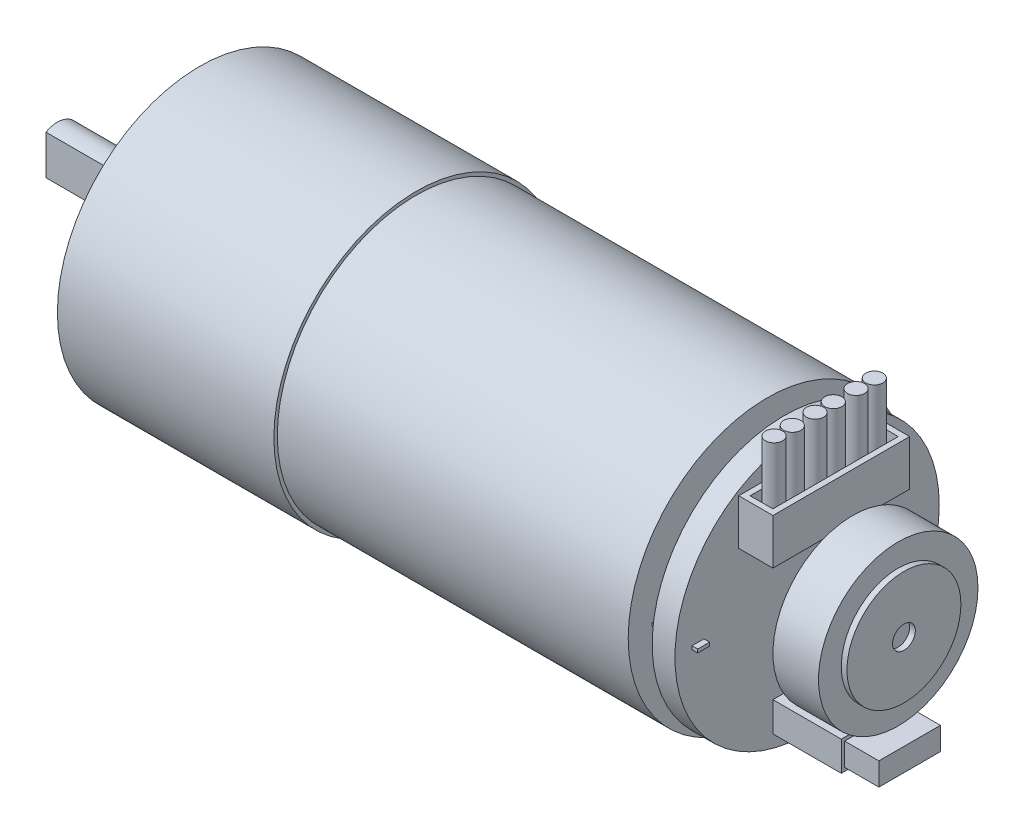
SolidWorks part; units mm, degrees
ref_plane "Alzado" through (0, 0, 0) normal (0, 0, 1) x (1, 0, 0)
ref_plane "Planta" through (0, 0, 0) normal (0, 1, 0) x (1, 0, 0)
ref_plane "Vista lateral" through (0, 0, 0) normal (1, 0, 0) x (0, 0, -1)
sketch "Croquis1" plane through (0, 0, 0) normal (0, 0, 1) x (1, 0, 0)
  line L0 (0, 0) -> (30.8, 0) construction
  line L1 (0, 0) -> (0, 12.2)
  line L2 (0, 12.2) -> (30.8, 12.2)
  line L3 (30.8, 12.2) -> (30.8, 0)
  dimension "D1" = 30.8
  dimension "D2" = 12.2
revolve "Revolución-Lámina1" add sketch "Croquis1" angle 360 about L0
sketch "Croquis3" plane through (0, 0, 0) normal (-1, 0, 0) x (0, 0, 1)
  circle A0 centre (0, 0) radius 12.5
  dimension "D1" = 25
extrude "Saliente-Extruir1" add sketch "Croquis3" along normal blind 19
ref_plane "Plano1" through (30.8, 0, 0) normal (1, 0, 0) x (0, 0, -1)
ref_plane "Plano3" through (-19, 0, 0) normal (1, 0, 0) x (0, 0, -1)
ref_plane "Plano4" through (-15.5, 0, 0) normal (1, 0, 0) x (0, 0, -1)
sketch "Croquis6" plane through (-15.5, 0, 0) normal (1, 0, 0) x (0, 0, -1)
  circle A0 centre (0, 0) radius 12
  circle A1 centre (0, 0) radius 12.5
  dimension "D1" = 24
  dimension "D2" = 25
extrude "Cortar-Extruir3" [suppressed] cut sketch "Croquis6" against normal blind 1
ref_plane "Plano5" through (-1.5, 0, 0) normal (1, 0, 0) x (0, 0, -1)
sketch "Croquis7" plane through (-1.5, 0, 0) normal (1, 0, 0) x (0, 0, -1)
  circle A0 centre (0, 0) radius 12.5
  circle A1 centre (0, 0) radius 12
  dimension "D1" = 24
  dimension "D2" = 25
extrude "Cortar-Extruir4" [suppressed] cut sketch "Croquis7" against normal blind 1
sketch "Croquis8" plane through (-19, 0, 0) normal (-1, 0, 0) x (0, 0, 1)
  circle A0 centre (0, 0) radius 3.5
  dimension "D1" = 7
extrude "Saliente-Extruir3" add sketch "Croquis8" along normal blind 2.5
sketch "Croquis9" plane through (-19, 0, 0) normal (-1, 0, 0) x (0, 0, 1)
  circle A0 centre (0, 0) radius 2
  dimension "D1" = 4
extrude "Saliente-Extruir4" add sketch "Croquis9" along normal blind 12.5
ref_plane "Plano6" through (0, 0, 1) normal (0, 0, 1) x (1, 0, 0)
sketch "Croquis10" plane through (0, 0, 1) normal (0, 0, 1) x (1, 0, 0)
  line L0 (-31.5, -2) -> (-21.5, -2) construction
  line L1 (-31.5, 2) -> (-23.5, 2)
  line L2 (-31.5, 2) -> (-31.5, -2)
  line L3 (-31.5, -2) -> (-23.5, -2)
  line L4 (-23.5, 2) -> (-23.5, -2)
  dimension "D1" = 8
extrude "Cortar-Extruir5" cut sketch "Croquis10" along normal blind 5
sketch "Croquis11" plane through (-19, 0, 0) normal (-1, 0, 0) x (0, 0, 1)
  line L0 (0, 0) -> (-8, 0) construction
  line L1 (0, 0) -> (8, 0) construction
  circle A0 centre (-8, 0) radius 1.5
  circle A1 centre (8, 0) radius 1.5
  dimension "D3" = 3
  dimension "D4" = 3
  dimension "D1" = 8
  dimension "D2" = 8
extrude "Cortar-Extruir6" cut sketch "Croquis11" against normal blind 3
sketch "Croquis12" plane through (-19, 0, 0) normal (-1, 0, 0) x (0, 0, 1)
  line L0 (0, 0) -> (0, -8.5) construction
  line L1 (0, 0) -> (0, 8.5) construction
  circle A0 centre (0, -8.5) radius 2
  circle A1 centre (0, 8.5) radius 2
  dimension "D3" = 4
  dimension "D4" = 4
  dimension "D1" = 8.5
  dimension "D2" = 8.5
extrude "Cortar-Extruir7" cut sketch "Croquis12" against normal blind 3
sketch "Croquis14" plane through (-16, 0, 0) normal (-1, 0, 0) x (0, 0, 1)
  line L0 (0, 8.5) -> (-0.25, 8.5) construction
  line L1 (0, 8.5) -> (0.25, 8.5) construction
  line L2 (0, 8.5) -> (0, 8.75) construction
  line L3 (0, 8.5) -> (0, 8.25) construction
  line L9 (-0.25, 8.25) -> (-0.25, 7.2)
  line L10 (-0.25, 7.2) -> (0.25, 7.2)
  line L11 (0.25, 7.2) -> (0.25, 8.25)
  line L12 (0.25, 8.25) -> (1.3, 8.25)
  line L13 (1.3, 8.25) -> (1.3, 8.75)
  line L14 (1.3, 8.75) -> (0.25, 8.75)
  line L15 (0.25, 8.75) -> (0.25, 9.8)
  line L16 (0.25, 9.8) -> (-0.25, 9.8)
  line L17 (-0.25, 9.8) -> (-0.25, 8.75)
  line L18 (-0.25, 8.75) -> (-1.3, 8.75)
  line L19 (-1.3, 8.75) -> (-1.3, 8.25)
  line L20 (-1.3, 8.25) -> (-0.25, 8.25)
extrude "Cortar-Extruir8" cut sketch "Croquis14" against normal blind 1.5
sketch "Croquis15" plane through (-16, 0, 0) normal (-1, 0, 0) x (0, 0, 1)
  line L0 (0, -8.5) -> (-0.25, -8.5) construction
  line L1 (0, -8.5) -> (0.25, -8.5) construction
  line L2 (0, -8.5) -> (0, -8.25) construction
  line L3 (0, -8.5) -> (0, -8.75) construction
  line L9 (-0.25, -8.75) -> (-0.25, -9.8)
  line L10 (-0.25, -9.8) -> (0.25, -9.8)
  line L11 (0.25, -9.8) -> (0.25, -8.75)
  line L12 (0.25, -8.75) -> (1.3, -8.75)
  line L13 (1.3, -8.75) -> (1.3, -8.25)
  line L14 (1.3, -8.25) -> (0.25, -8.25)
  line L15 (0.25, -8.25) -> (0.25, -7.2)
  line L16 (0.25, -7.2) -> (-0.25, -7.2)
  line L17 (-0.25, -7.2) -> (-0.25, -8.25)
  line L18 (-0.25, -8.25) -> (-1.3, -8.25)
  line L19 (-0.25, -8.75) -> (-1.3, -8.75)
  line L20 (-1.3, -8.75) -> (-1.3, -8.25)
  dimension "D1" = 1.05
  dimension "D2" = 0.25
  dimension "D3" = 1.05
  dimension "D4" = 1.05
  dimension "D5" = 1.05
extrude "Cortar-Extruir9" cut sketch "Croquis15" against normal blind 1.5
fillet "Redondeo1" radius 0.25 2 edges at (-16, 8.5, 2) (-16, -8.5, 2)
sketch "Croquis16" plane through (30.8, 0, 0) normal (1, 0, 0) x (0, 0, -1)
  line L0 (0, 0) -> (-9.05, 0) construction
  line L1 (0, 0) -> (9.05, 0) construction
  line L2 (8, -0.15) -> (8, 0.15)
  line L3 (-9.05, 0) -> (-8, 0)
  line L5 (9.05, 0) -> (10.1, 0)
  line L6 (-10.1, -0.15) -> (-10.1, 0.15)
  line L7 (-10.1, 0.15) -> (-9.05, 0.15)
  line L8 (-9.05, 0.15) -> (-9.05, -0.15)
  line L9 (-9.05, -0.15) -> (-10.1, -0.15)
  line L10 (8, 0.15) -> (9.05, 0.15)
  line L11 (9.05, 0.15) -> (9.05, -0.15)
  line L12 (9.05, -0.15) -> (8, -0.15)
  dimension "D1" = 9.05
  dimension "D2" = 9.05
extrude "Saliente-Extruir5" add sketch "Croquis16" along normal blind 4 contours L9 L8 L7 L6 | L12 L11 L10 L2
sketch "Croquis17" plane through (30.8, 0, 0) normal (1, 0, 0) x (0, 0, -1)
  circle A0 centre (0, 0) radius 4
  dimension "D1" = 8
extrude "Saliente-Extruir6" add sketch "Croquis17" along normal blind 0.75
sketch "Croquis18" plane through (31.55, 0, 0) normal (1, 0, 0) x (0, 0, -1)
  circle A0 centre (0, 0) radius 3.5
  dimension "D1" = 7
extrude "Saliente-Extruir7" add sketch "Croquis18" along normal blind 0.75
sketch "Croquis19" plane through (32.3, 0, 0) normal (1, 0, 0) x (0, 0, -1)
  circle A0 centre (0, 0) radius 11.6
  dimension "D1" = 23.2
extrude "Saliente-Extruir8" add sketch "Croquis19" along normal blind 2
sketch "Croquis20" plane through (34.3, 0, 0) normal (1, 0, 0) x (0, 0, -1)
  circle A0 centre (0, 0) radius 1
  dimension "D1" = 2
extrude "Saliente-Extruir9" add sketch "Croquis20" along normal blind 4
sketch "Croquis21" plane through (38.3, 0, 0) normal (1, 0, 0) x (0, 0, -1)
  circle A0 centre (0, 0) radius 7
  dimension "D1" = 14
extrude "Saliente-Extruir10" add sketch "Croquis21" along normal blind 4
sketch "Croquis22" plane through (42.3, 0, 0) normal (1, 0, 0) x (0, 0, -1)
  circle A0 centre (0, 0) radius 5
  dimension "D1" = 10
extrude "Saliente-Extruir11" add sketch "Croquis22" along normal blind 0.5
sketch "Croquis23" plane through (42.8, 0, 0) normal (1, 0, 0) x (0, 0, -1)
  circle A0 centre (0, 0) radius 1
  dimension "D1" = 2
extrude "Cortar-Extruir10" cut sketch "Croquis23" against normal blind 0.5
sketch "Croquis24" plane through (34.3, 0, 0) normal (1, 0, 0) x (0, 0, -1)
  line L0 (0, 11.6) -> (0, 9.5) construction
  line L1 (0, 9.5) -> (6, 9.5)
  line L2 (0, 9.5) -> (-6, 9.5)
  line L3 (-6, 9.5) -> (-6, 5.5)
  line L4 (-6, 5.5) -> (6, 5.5)
  line L5 (6, 5.5) -> (6, 9.5)
  circle A0 centre (0, 0) radius 11.6 construction
  dimension "D1" = 2.1
  dimension "D2" = 6
  dimension "D3" = 6
  dimension "D4" = 4
extrude "Saliente-Extruir12" add sketch "Croquis24" along normal blind 3
sketch "Croquis25" plane through (0, 9.5, 0) normal (0, 1, 0) x (1, 0, 0)
  line L0 (35.8, -6) -> (35.8, -5.5) construction
  line L1 (37.3, -6) -> (34.3, -6) construction
  line L2 (37.3, 0) -> (36.8, 0) construction
  line L3 (37.3, 6) -> (37.3, -6) construction
  line L4 (36.8, -5.5) -> (36.8, 5.5)
  line L5 (35.8, -5.5) -> (36.8, -5.5)
  line L6 (36.8, 5.5) -> (34.8, 5.5)
  line L7 (35.8, 6) -> (35.8, 5.5) construction
  line L8 (37.3, 6) -> (34.3, 6) construction
  line L9 (34.8, 5.5) -> (34.8, -5.5)
  line L10 (34.8, -5.5) -> (35.8, -5.5)
  dimension "D1" = 0.5
  dimension "D2" = 0.5
  dimension "D3" = 0.5
  dimension "D4" = 2
extrude "Cortar-Extruir11" cut sketch "Croquis25" against normal blind 3.5
sketch "Croquis26" plane through (0, 6, 0) normal (0, 1, 0) x (1, 0, 0)
  line L0 (35.8, -5.5) -> (35.8, -4.4) construction
  line L1 (34.8, -5.5) -> (36.8, -5.5) construction
  line L2 (35.8, -4.4) -> (35.8, -2.8) construction
  line L3 (35.8, -2.8) -> (35.8, -0.8) construction
  line L4 (35.8, -0.8) -> (35.8, 0.8) construction
  line L5 (35.8, 0.8) -> (35.8, 2.8) construction
  line L6 (35.8, 2.8) -> (35.8, 4.4) construction
  circle A0 centre (35.8, -4.4) radius 0.75
  circle A1 centre (35.8, -2.8) radius 0.75
  circle A2 centre (35.8, -0.8) radius 0.75
  circle A3 centre (35.8, 0.8) radius 0.75
  circle A4 centre (35.8, 2.8) radius 0.75
  circle A5 centre (35.8, 4.4) radius 0.75
  dimension "D2" = 1.5
  dimension "D4" = 1.5
  dimension "D6" = 1.5
  dimension "D8" = 1.5
  dimension "D10" = 1.5
  dimension "D12" = 1.5
  dimension "D1" = 1.1
  dimension "D3" = 1.6
  dimension "D5" = 2
  dimension "D7" = 1.6
  dimension "D9" = 2
  dimension "D11" = 1.6
extrude "Saliente-Extruir13" add sketch "Croquis26" along normal blind 8
sketch "Croquis27" plane through (34.3, 0, 0) normal (1, 0, 0) x (0, 0, -1)
  line L0 (0, -11.6) -> (0, -10.1) construction
  line L1 (0, -10.1) -> (3, -10.1)
  line L2 (0, -10.1) -> (-3, -10.1)
  line L3 (-3, -10.1) -> (-3, -7.5)
  line L4 (-3, -7.5) -> (3, -7.5)
  line L5 (3, -7.5) -> (3, -10.1)
  circle A0 centre (0, 0) radius 11.6 construction
  dimension "D1" = 1.5
  dimension "D2" = 3
  dimension "D3" = 3
  dimension "D4" = 2.6
extrude "Saliente-Extruir14" add sketch "Croquis27" along normal blind 6
sketch "Croquis28" plane through (40.3, 0, 0) normal (1, 0, 0) x (0, 0, -1)
  line L0 (3, -7.5) -> (-3, -7.5) construction
  line L1 (-2.7, -7.8) -> (2.7, -7.8)
  line L2 (-2.7, -7.8) -> (-2.7, -9.8)
  line L3 (-2.7, -9.8) -> (2.7, -9.8)
  line L4 (2.7, -7.8) -> (2.7, -9.8)
  line L5 (-3, -7.5) -> (-3, -10.1) construction
  line L6 (-3, -10.1) -> (3, -10.1) construction
  line L7 (3, -10.1) -> (3, -7.5) construction
  dimension "D1" = 0.3
  dimension "D2" = 0.3
  dimension "D3" = 0.3
  dimension "D4" = 0.3
extrude "Saliente-Extruir15" add sketch "Croquis28" along normal blind 3
